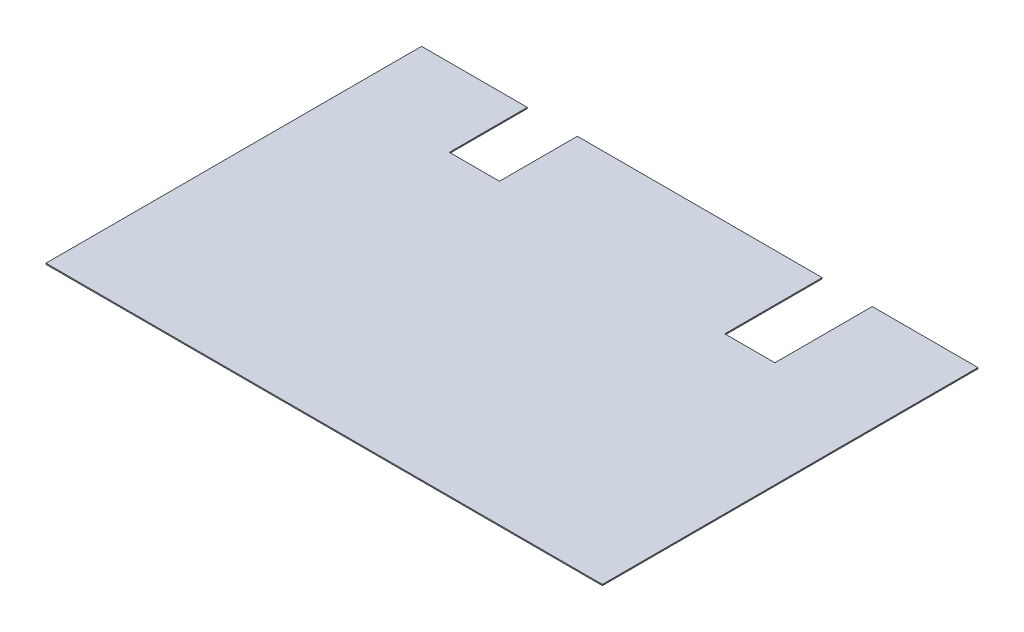
SolidWorks part; units mm, degrees
ref_plane "Front Plane" through (0, 0, 0) normal (0, 0, 1) x (1, 0, 0)
ref_plane "Top Plane" through (0, 0, 0) normal (0, 1, 0) x (1, 0, 0)
ref_plane "Right Plane" through (0, 0, 0) normal (1, 0, 0) x (0, 0, -1)
sketch "Sketch1" plane through (0, 0, 0) normal (0, 1, 0) x (1, 0, 0)
  line L1 (0, 0) -> (25.4, 0)
  line L2 (0, 0) -> (0, 17.145)
  line L3 (0, 17.145) -> (25.4, 17.145)
  line L4 (25.4, 0) -> (25.4, 17.145)
  dimension "D1" = 25.4
  dimension "D2" = 17.145
extrude "Boss-Extrude1" add sketch "Sketch1" along normal blind 0.0508
sketch "Sketch2" plane through (0, 0.0508, 0) normal (0, 1, 0) x (1, 0, 0)
  line L0 (25.4, 17.145) -> (0, 17.145) construction
  line L1 (6.0325, 17.145) -> (7.112, 17.145)
  line L2 (4.826, 14.605) -> (4.826, 13.589)
  line L3 (4.826, 13.589) -> (7.112, 13.589)
  line L4 (7.112, 17.145) -> (7.112, 13.589)
  line L5 (0, 0) -> (25.4, 0) construction
  line L6 (18.288, 17.145) -> (19.3675, 17.145)
  line L7 (18.288, 17.145) -> (18.288, 12.7)
  line L8 (18.288, 12.7) -> (20.574, 12.7)
  line L9 (20.574, 13.589) -> (20.574, 12.7)
  line L10 (0, 0) -> (25.4, 0) construction
  line L13 (20.574, 13.589) -> (20.574, 17.145)
  line L14 (20.574, 17.145) -> (19.3675, 17.145)
  line L15 (4.826, 14.605) -> (4.826, 17.145)
  line L16 (4.826, 17.145) -> (6.0325, 17.145)
  point P10 (12.7, 0)
  point P13 (12.7, 0)
  dimension "D3" = 2.286
  dimension "D4" = 2.286
  dimension "D5" = 5.588
  dimension "D6" = 5.588
extrude "Cut-Extrude1" cut sketch "Sketch2" against normal through all
